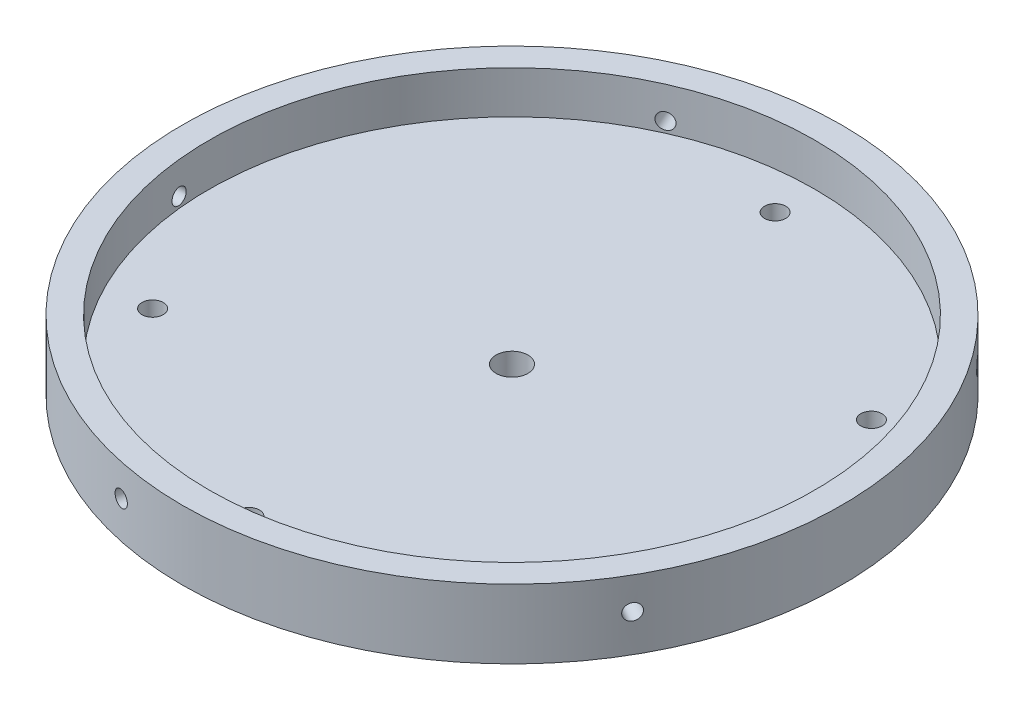
SolidWorks part; units mm, degrees
material "Polyetheretherketone (PEEK)"
ref_plane "Front Plane" through (0, 0, 0) normal (0, 0, 1) x (1, 0, 0)
ref_plane "Top Plane" through (0, 0, 0) normal (0, 1, 0) x (1, 0, 0)
ref_plane "Right Plane" through (0, 0, 0) normal (1, 0, 0) x (0, 0, -1)
sketch "Sketch1" plane through (0, 0, 0) normal (0, 1, 0) x (1, 0, 0)
  circle A0 centre (0, 0) radius 62
  dimension "D1" = 124
extrude "Boss-Extrude1" add sketch "Sketch1" along normal blind 5
sketch "Sketch2" plane through (0, 5, 0) normal (0, 1, 0) x (1, 0, 0)
  circle A0 centre (0, 49.5) radius 2
  dimension "D2" = 4
  dimension "D1" = 49.5
extrude "Cut-Extrude1" cut sketch "Sketch2" against normal blind 5 contours A0
pattern_circular "CirPattern1" count 2 every 120 about axis through (0, 5, 0) along (0, 1, 0) of "Cut-Extrude1"
sketch "Sketch4" plane through (0, 5, 0) normal (0, 1, 0) x (1, 0, 0)
  line L0 (0, 49.5) -> (-42.8683, -24.75) construction
  line L1 (0, 0) -> (-23.6703, -40.9981) construction
ref_plane "Plane1" through (0, 0, 0) normal (-0.866, 0, -0.5) x (-0.5, 0, 0.866)
mirror "Mirror1" about plane through (0, 0, 0) normal (-0.866, 0, -0.5) of "Cut-Extrude1", "CirPattern1"
sketch "Sketch5" plane through (0, 5, 0) normal (0, 1, 0) x (1, 0, 0)
  circle A0 centre (0, 0) radius 62
  circle A1 centre (0, 0) radius 57
  dimension "D1" = 5
extrude "Boss-Extrude2" add sketch "Sketch5" along normal blind 8
sketch "Sketch6" plane through (0, 0, 0) normal (-0.866, 0, -0.5) x (-0.5, 0, 0.866)
  line L0 (57, 13) -> (-57, 13) construction
  circle A0 centre (0, 7) radius 1.5
  dimension "D1" = 3
  dimension "D2" = 6
extrude "Cut-Extrude2" cut sketch "Sketch6" against normal blind 90 and the other way blind 1 contours A0
pattern_circular "CirPattern2" count 5 every 72 about axis through (0, 13, 0) along (0, 1, 0) of "Cut-Extrude2"
sketch "Sketch7" plane through (0, 5, 0) normal (0, 1, 0) x (1, 0, 0)
  circle A0 centre (0, 0) radius 3
  dimension "D1" = 6
extrude "Cut-Extrude3" cut sketch "Sketch7" against normal blind 10
sketch "Sketch9" plane through (0, 0, 0) normal (0, 1, 0) x (1, 0, 0)
  line L0 (0, 0) -> (53.6936, -31)
  line L2 (53.6936, -31) -> (85.1545, 23.4919) construction
ref_plane "Plane2" through (0, 0, 0) normal (0.866, 0, 0.5) x (-0.5, 0, 0.866)
ref_plane "Plane3" through (34.641, 0, 20) normal (0.866, 0, 0.5) x (-0.5, 0, 0.866)
sketch "Sketch10" plane through (0, 5, 0) normal (0, 1, 0) x (1, 0, 0)
  circle A0 centre (0, 0) radius 57
